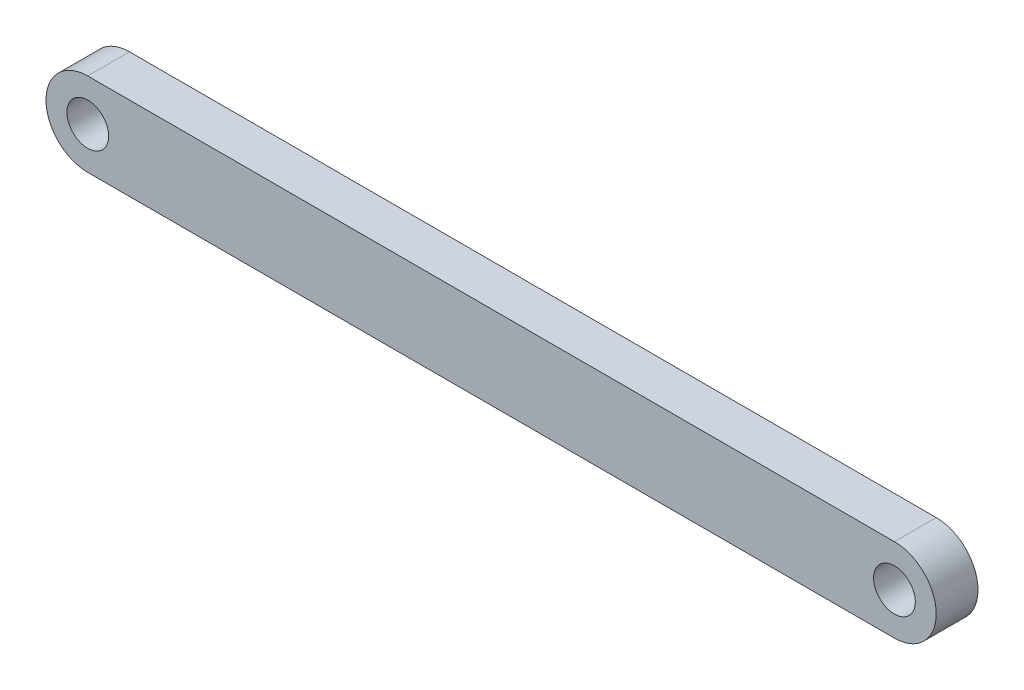
SolidWorks part; units mm, degrees
ref_plane "Plano frontal" through (0, 0, 0) normal (0, 0, 1) x (1, 0, 0)
ref_plane "Plano superior" through (0, 0, 0) normal (0, 1, 0) x (1, 0, 0)
ref_plane "Plano direito" through (0, 0, 0) normal (1, 0, 0) x (0, 0, -1)
sketch "Esboço1" plane through (0, 0, 0) normal (0, 0, 1) x (1, 0, 0)
  line L0 (-83.96, 5) -> (12.58, 5)
  line L2 (-83.96, -5) -> (12.58, -5)
  arc A0 (-83.96, 5) -> (-83.96, -5) centre (-83.96, 0) ccw
  arc A1 (12.58, 5) -> (12.58, -5) centre (12.58, 0) cw
  circle A2 centre (-83.96, 0) radius 2.5
  circle A4 centre (12.58, 0) radius 2.5
  point P3 (-35.69, 5)
  dimension "D1" = 96.54
  dimension "D2" = 5
extrude "Ressalto-extrusão1" add sketch "Esboço1" along normal blind 5
